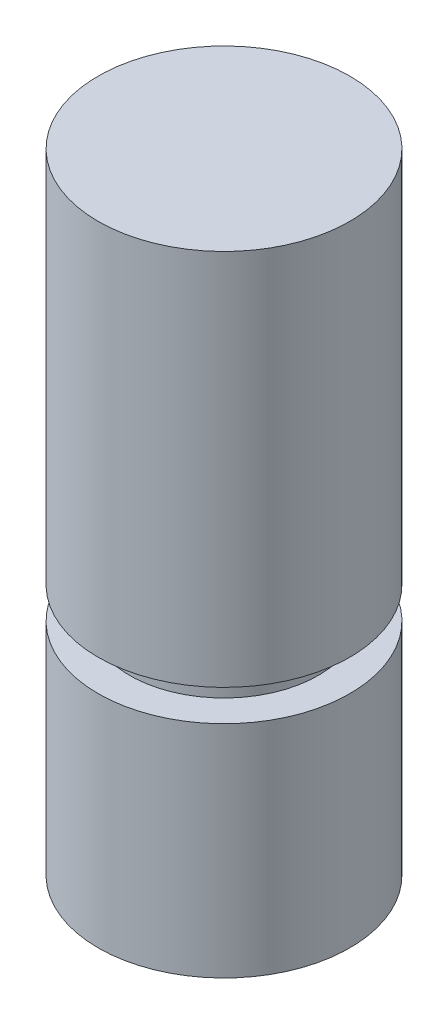
SolidWorks part; units mm, degrees
ref_plane "Front Plane" through (0, 0, 0) normal (0, 0, 1) x (1, 0, 0)
ref_plane "Top Plane" through (0, 0, 0) normal (0, 1, 0) x (1, 0, 0)
ref_plane "Right Plane" through (0, 0, 0) normal (1, 0, 0) x (0, 0, -1)
sketch "Sketch1" plane through (0, 0, 0) normal (0, 1, 0) x (1, 0, 0)
  circle A0 centre (0, 0) radius 2
  dimension "D1" = 4
extrude "Boss-Extrude1" add sketch "Sketch1" along normal blind 10
sketch "Sketch2" plane through (0, 0, 0) normal (0, 0, 1) x (1, 0, 0)
  line L0 (2, 0) -> (2, 10) construction
  line L1 (2, 4) -> (1.5, 4)
  line L2 (2, 4) -> (2, 3.5)
  line L3 (2, 3.5) -> (1.5, 3.5)
  line L4 (1.5, 4) -> (1.5, 3.5)
  line L5 (2, 10) -> (-2, 10) construction
  line L6 (0, 0) -> (0, 10.2745) construction
  dimension "D1" = 0.5
  dimension "D2" = 0.5
  dimension "D3" = 6
revolve "Cut-Revolve1" cut sketch "Sketch2" angle 360 about L6
